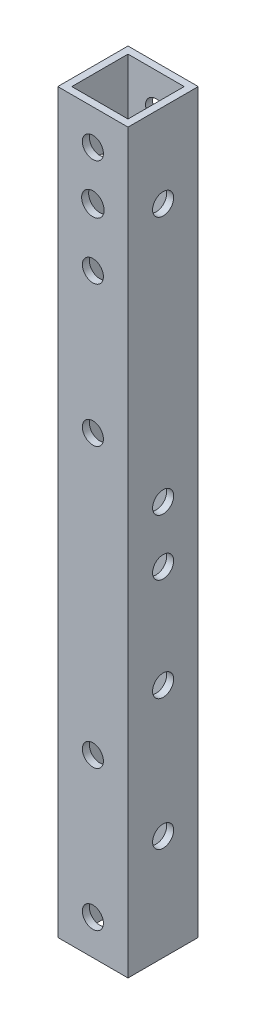
SolidWorks part; units mm, degrees
material "1060 合金"
ref_plane "正面" through (0, 0, 0) normal (0, 0, 1) x (1, 0, 0)
ref_plane "平面" through (0, 0, 0) normal (0, 1, 0) x (1, 0, 0)
ref_plane "右側面" through (0, 0, 0) normal (1, 0, 0) x (0, 0, -1)
sketch "ｽｹｯﾁ1" plane through (0, 0, 0) normal (0, 1, 0) x (1, 0, 0)
  line L1 (-5, -5) -> (5, -5)
  line L2 (-5, -5) -> (-5, 5)
  line L3 (-5, 5) -> (5, 5)
  line L4 (5, -5) -> (5, 5)
  line L5 (-5, -5) -> (5, 5) construction
  line L6 (-5, 5) -> (5, -5) construction
  point P0 (0, 0)
  dimension "D1" = 10
extrude "押し出し-薄板1" add sketch "ｽｹｯﾁ1" along normal blind 104.9 thin thin type one direction reverse wall 1
sketch "ｽｹｯﾁ2" plane through (0, 0, 5) normal (0, 0, 1) x (1, 0, 0)
  line L0 (0, 0) -> (0, 50000) construction
  line L1 (-5, 0) -> (5, 0) construction
  line L2 (-5, 104.9) -> (5, 104.9) construction
  circle A1 centre (0, 5) radius 1.5
  circle A5 centre (0, 64.7) radius 1.5
  circle A6 centre (0, 99.9) radius 1.5
  circle A7 centre (0, 84.7) radius 1.5
  circle A8 centre (0, 25) radius 1.5
  circle A9 centre (0, 92.95) radius 1.6
  dimension "D1" = 5
  dimension "D2" = 3
  dimension "D3" = 35.2
  dimension "D4" = 20
  dimension "D5" = 3
  dimension "D6" = 20
  dimension "D7" = 5
  dimension "D8" = 3
  dimension "D9" = 3
  dimension "D10" = 8.25
  dimension "D11" = 3.2
extrude "ｶｯﾄ - 押し出し1" cut sketch "ｽｹｯﾁ2" against normal through all
sketch "ｽｹｯﾁ3" plane through (5, 0, 0) normal (1, 0, 0) x (0, 0, -1)
  line L0 (0, 0) -> (0, 104.9) construction
  line L1 (-5, 104.9) -> (5, 104.9) construction
  line L2 (0, 33.6) -> (5, 33.6) construction
  line L3 (5, 104.9) -> (5, 0) construction
  line L4 (-5, 0) -> (5, 0) construction
  circle A4 centre (0, 33.6) radius 1.5
  circle A9 centre (0, 15) radius 1.5
  circle A11 centre (0, 48.2) radius 1.5
  circle A12 centre (0, 56.2) radius 1.5
  circle A13 centre (0, 92.95) radius 1.5
  dimension "D1" = 15
  dimension "D2" = 48.2
  dimension "D3" = 3
  dimension "D4" = 8
  dimension "D5" = 18.6
  dimension "D6" = 11.95
  dimension "D7" = 3
  dimension "D8" = 3
extrude "ｶｯﾄ - 押し出し2" cut sketch "ｽｹｯﾁ3" against normal through all
